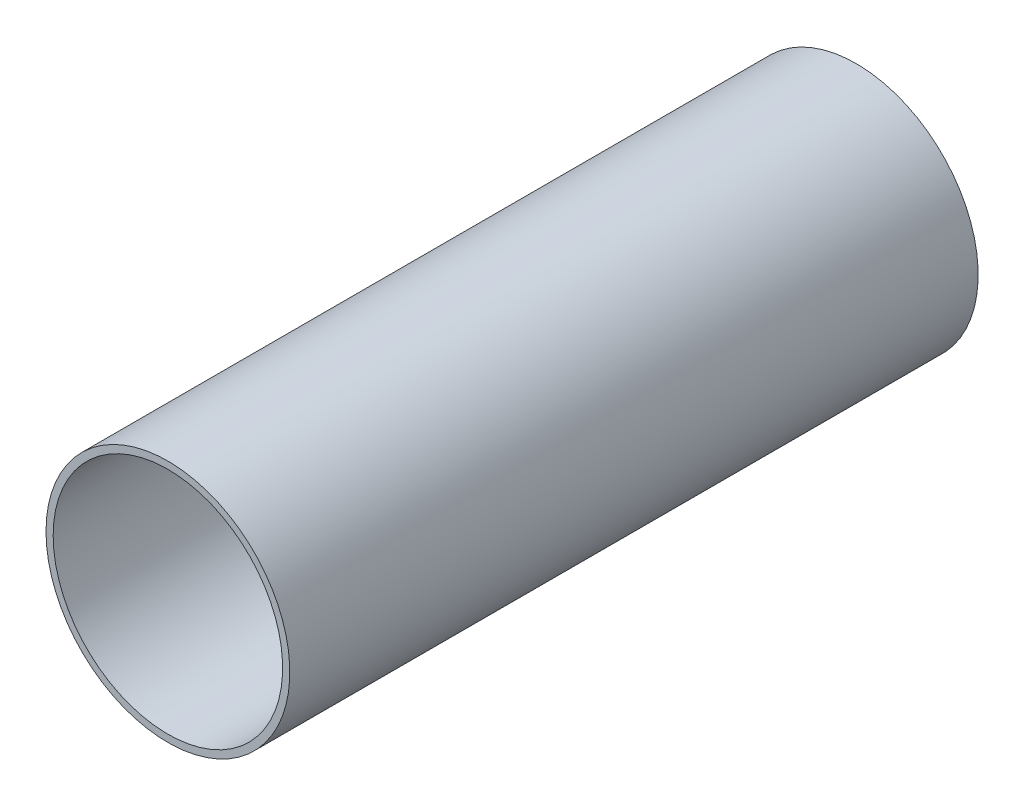
SolidWorks part; units mm, degrees
material "Acrylic (Medium-high impact)"
ref_plane "Front Plane" through (0, 0, 0) normal (0, 0, 1) x (1, 0, 0)
ref_plane "Top Plane" through (0, 0, 0) normal (0, 1, 0) x (1, 0, 0)
ref_plane "Right Plane" through (0, 0, 0) normal (1, 0, 0) x (0, 0, -1)
sketch "Sketch2" plane through (0, 0, 0) normal (0, 0, 1) x (1, 0, 0)
  circle A0 centre (0, 0) radius 101.6
  circle A1 centre (0, 0) radius 107.95
  dimension "D1" = 203.2
  dimension "D2" = 6.35
extrude "Boss-Extrude1" add sketch "Sketch2" along normal blind 609.6
